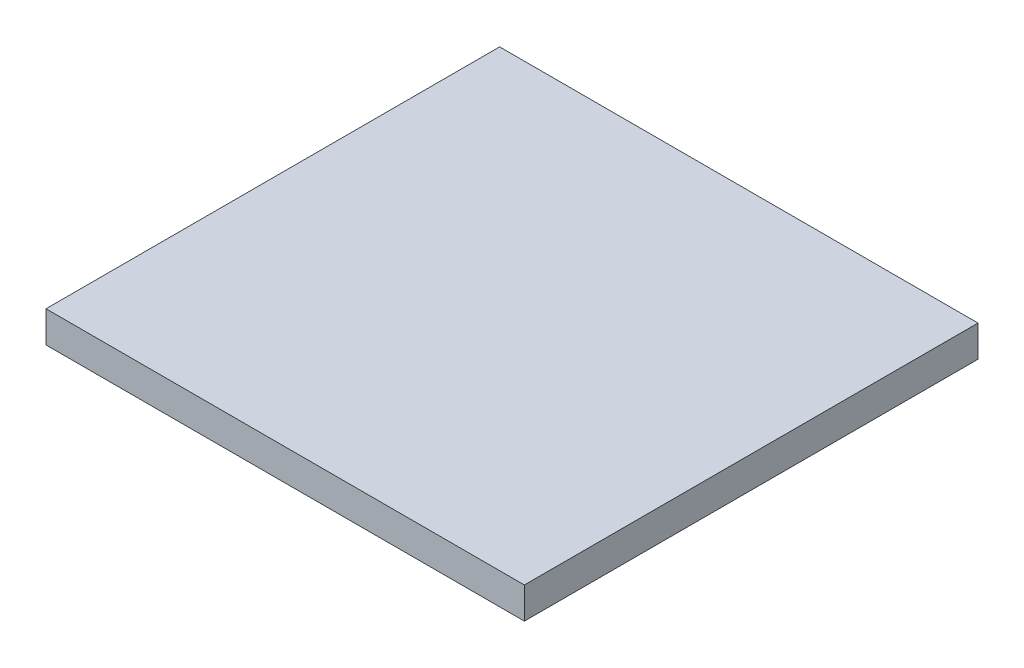
SolidWorks part; units mm, degrees
ref_plane "Front Plane" through (0, 0, 0) normal (0, 0, 1) x (1, 0, 0)
ref_plane "Top Plane" through (0, 0, 0) normal (0, 1, 0) x (1, 0, 0)
ref_plane "Right Plane" through (0, 0, 0) normal (1, 0, 0) x (0, 0, -1)
other "Configuration Table"
sketch "Sketch1" plane through (0, 0, 0) normal (0, 0, 1) x (1, 0, 0)
  line L1 (60, 1080) -> (640, 1080)
  line L2 (60, 1080) -> (60, 1118)
  line L3 (60, 1118) -> (640, 1118)
  line L4 (640, 1080) -> (640, 1118)
extrude "OVEN_sicak_dolap_pu_ust_1" add sketch "Sketch1" against normal blind 550 from offset 30 separate body
